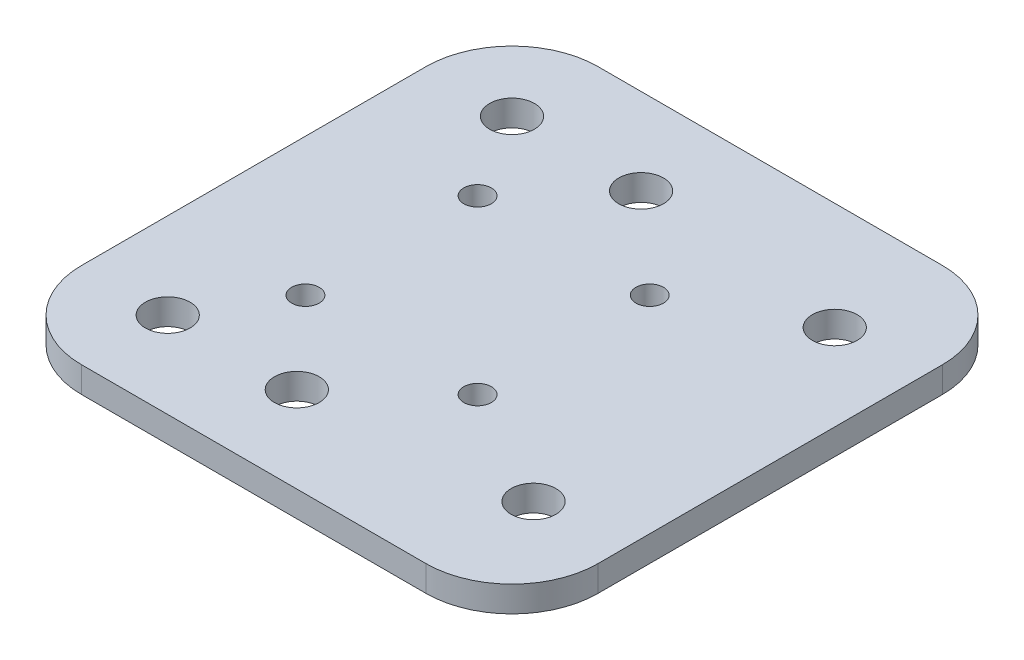
SolidWorks part; units mm, degrees
material "Thornel Mat VMA"
ref_plane "Front" through (0, 0, 0) normal (0, 0, 1) x (1, 0, 0)
ref_plane "Top" through (0, 0, 0) normal (0, 1, 0) x (1, 0, 0)
ref_plane "Right" through (0, 0, 0) normal (1, 0, 0) x (0, 0, -1)
sketch "草图1" plane through (0, 0, 0) normal (0, 1, 0) x (1, 0, 0)
  line L0 (0, -30) -> (0, 30)
  line L1 (0, 30) -> (21.7157, 30)
  line L2 (21.7157, 30) -> (60, 30)
  line L3 (60, 30) -> (60, -30)
  line L4 (0, 0) -> (173.2794, 0) construction
  line L5 (21.7157, -30) -> (60, -30)
  line L6 (0, -30) -> (21.7157, -30)
  point P4 (0, 0)
  point P12 (60, 0)
  dimension "D1" = 60
  dimension "D2" = 30
  dimension "D3" = 60
extrude "凸台-拉伸1" add sketch "草图1" along normal blind 3
sketch "草图2" plane through (0, 3, 0) normal (0, 1, 0) x (1, 0, 0)
  line L0 (16, 10) -> (36, 10) construction
  line L1 (0, 0) -> (60, 0) construction
  line L2 (60, -30) -> (60, 30) construction
  line L4 (25, 20) -> (25, -20) construction
  line L5 (50, 17.5) -> (50, -17.5) construction
  line L6 (10, 20) -> (10, -20) construction
  line L7 (0, 30) -> (0, -30) construction
  line L8 (60, 30) -> (0, 30) construction
  line L9 (0, -30) -> (60, -30) construction
  line L10 (60, -30) -> (60, 30) construction
  circle A0 centre (16, 10) radius 1.6
  circle A1 centre (36, 10) radius 1.6
  circle A2 centre (36, -10) radius 1.6
  circle A3 centre (16, -10) radius 1.6
  circle A4 centre (10, 20) radius 2.6
  circle A5 centre (10, -20) radius 2.6
  circle A8 centre (25, 20) radius 2.6
  circle A9 centre (25, -20) radius 2.6
  circle A10 centre (50, 17.5) radius 2.6
  circle A11 centre (50, -17.5) radius 2.6
  point P31 (25, 0)
  point P33 (50, 0)
  dimension "D1" = 3.2
  dimension "D2" = 3.2
  dimension "D5" = 5.2
  dimension "D6" = 5.2
  dimension "D7" = 10
  dimension "D8" = 10
  dimension "D9" = 10
  dimension "D10" = 10
  dimension "D13" = 5.2
  dimension "D14" = 5.2
  dimension "D15" = 5.2
  dimension "D16" = 5.2
  dimension "D3" = 20
  dimension "D4" = 10
  dimension "D11" = 16
  dimension "D12" = 15
  dimension "D17" = 40
  dimension "D18" = 35
extrude "切除-拉伸1" cut sketch "草图2" against normal through all
fillet "圆角1" radius 10 4 edges at (0, 1.5, 30) (0, 1.5, -30) (60, 1.5, 30) (60, 1.5, -30)
